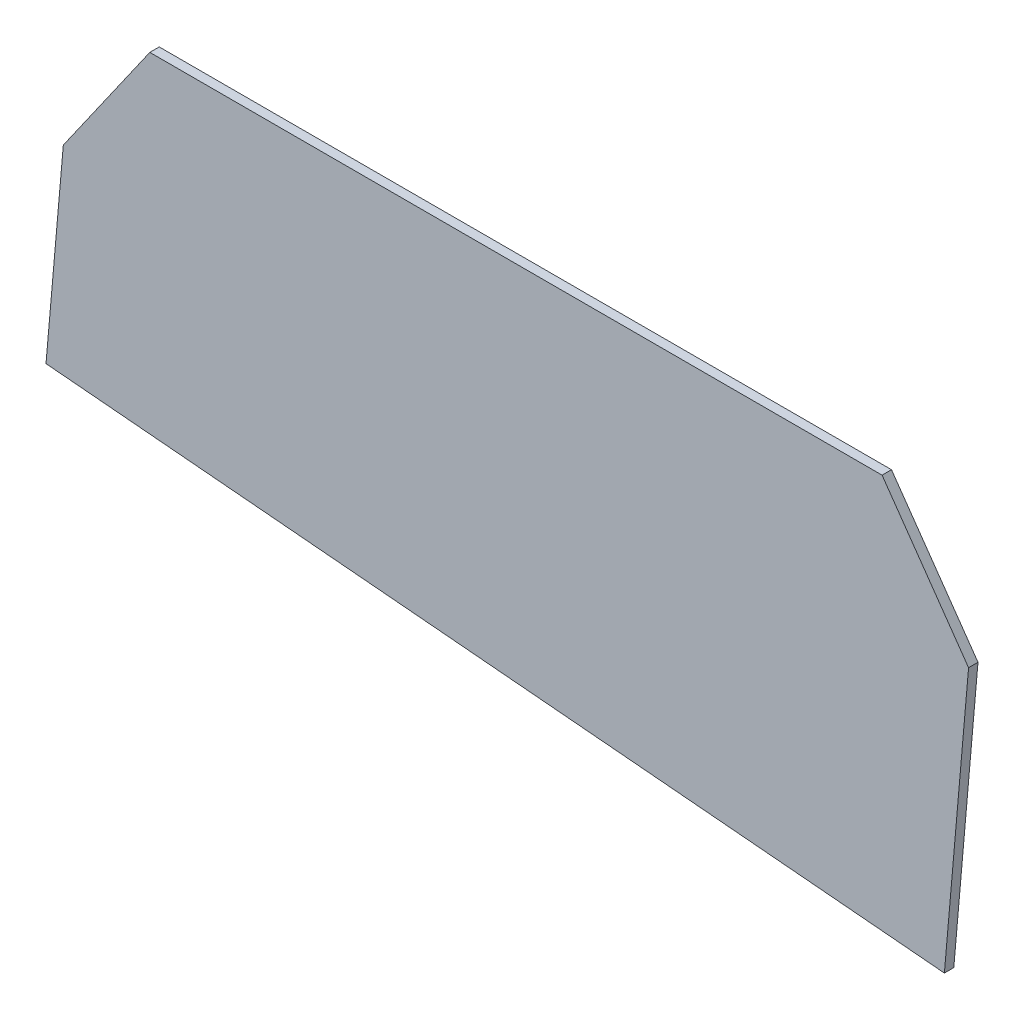
SolidWorks part; units mm, degrees
ref_plane "Front Plane" through (0, 0, 0) normal (0, 0, 1) x (1, 0, 0)
ref_plane "Top Plane" through (0, 0, 0) normal (0, 1, 0) x (1, 0, 0)
ref_plane "Right Plane" through (0, 0, 0) normal (1, 0, 0) x (0, 0, -1)
sketch "Sketch1" plane through (0, 0, 0) normal (0, 0, 1) x (1, 0, 0)
  line L0 (-79.8501, 25.4) -> (-50.7124, -16.2129)
  line L1 (-105.1599, -54.3375) -> (386.2158, 289.7275) construction
  line L2 (-50.7124, -16.2129) -> (-58.8636, -109.3819)
  line L3 (-569.8915, -64.6728) -> (50.1681, -118.9209) construction
  line L4 (-79.8501, 25.4) -> (-326.5499, 25.4)
  line L5 (-326.5499, 25.4) -> (-355.6876, -16.2129)
  line L6 (-329.2379, -34.7332) -> (-762.7793, 268.8357) construction
  line L7 (-355.6876, -16.2129) -> (-361.5222, -82.9027)
  line L8 (-361.5222, -82.9027) -> (-58.8636, -109.3819)
extrude "Boss-Extrude1" add sketch "Sketch1" along normal blind 3.175
